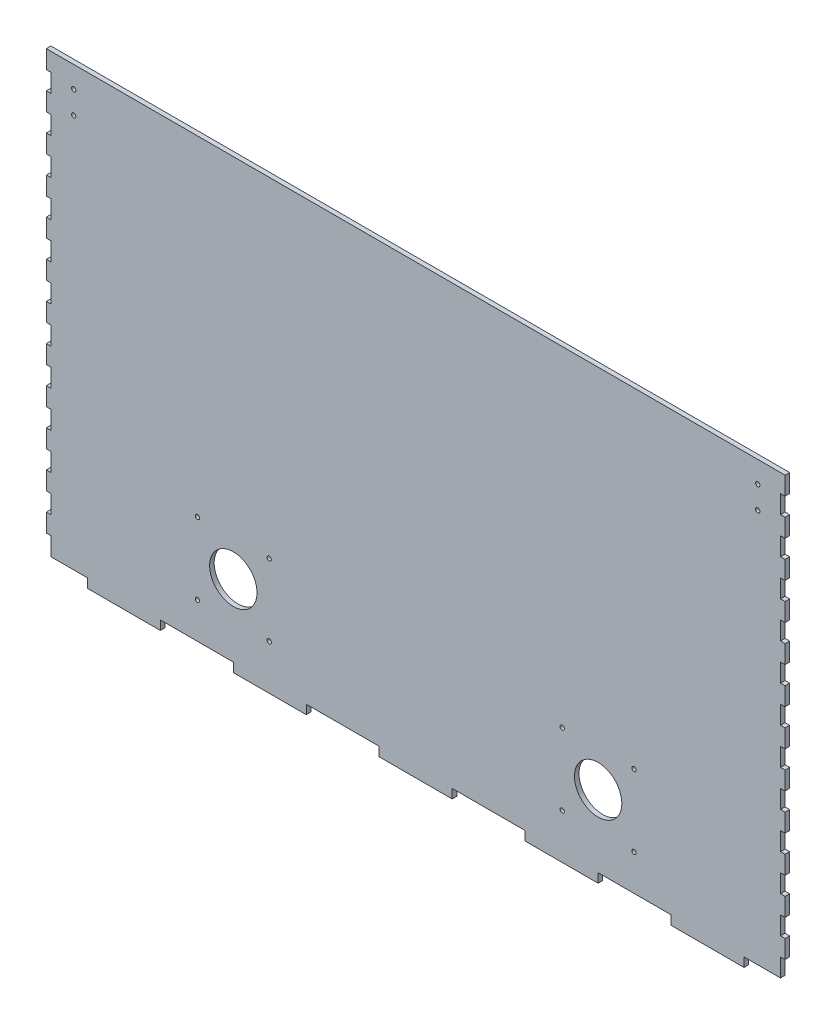
SolidWorks part; units mm, degrees
ref_plane "Front Plane" through (0, 0, 0) normal (0, 0, 1) x (1, 0, 0)
ref_plane "Top Plane" through (0, 0, 0) normal (0, 1, 0) x (1, 0, 0)
ref_plane "Right Plane" through (0, 0, 0) normal (1, 0, 0) x (0, 0, -1)
sketch "Sketch1" plane through (0, 0, 0) normal (0, 0, 1) x (1, 0, 0)
  line L0 (0, 0) -> (508, 0)
  line L1 (508, 0) -> (508, 304.8)
  line L2 (508, 304.8) -> (0, 304.8)
  line L3 (0, 304.8) -> (0, 0)
  line L4 (254, 304.8) -> (254, 0) construction
  line L5 (0, 304.8) -> (-3.175, 304.8)
  line L6 (-3.175, 304.8) -> (-3.175, 292.1)
  line L7 (-3.175, 292.1) -> (0, 292.1)
  line L8 (25.4, 0) -> (25.4, -6.35)
  line L9 (25.4, -6.35) -> (76.2, -6.35)
  line L10 (76.2, -6.35) -> (76.2, 0)
  line L13 (0, 279.4) -> (-3.175, 279.4)
  line L14 (-3.175, 279.4) -> (-3.175, 266.7)
  line L15 (-3.175, 266.7) -> (0, 266.7)
  line L17 (0, 254) -> (-3.175, 254)
  line L18 (-3.175, 254) -> (-3.175, 241.3)
  line L19 (-3.175, 241.3) -> (0, 241.3)
  line L21 (0, 228.6) -> (-3.175, 228.6)
  line L22 (-3.175, 228.6) -> (-3.175, 215.9)
  line L23 (-3.175, 215.9) -> (0, 215.9)
  line L25 (0, 203.2) -> (-3.175, 203.2)
  line L26 (-3.175, 203.2) -> (-3.175, 190.5)
  line L27 (-3.175, 190.5) -> (0, 190.5)
  line L29 (0, 177.8) -> (-3.175, 177.8)
  line L30 (-3.175, 177.8) -> (-3.175, 165.1)
  line L31 (-3.175, 165.1) -> (0, 165.1)
  line L33 (0, 152.4) -> (-3.175, 152.4)
  line L34 (-3.175, 152.4) -> (-3.175, 139.7)
  line L35 (-3.175, 139.7) -> (0, 139.7)
  line L37 (0, 127) -> (-3.175, 127)
  line L38 (-3.175, 127) -> (-3.175, 114.3)
  line L39 (-3.175, 114.3) -> (0, 114.3)
  line L41 (0, 101.6) -> (-3.175, 101.6)
  line L42 (-3.175, 101.6) -> (-3.175, 88.9)
  line L43 (-3.175, 88.9) -> (0, 88.9)
  line L45 (0, 76.2) -> (-3.175, 76.2)
  line L46 (-3.175, 76.2) -> (-3.175, 63.5)
  line L47 (-3.175, 63.5) -> (0, 63.5)
  line L49 (0, 50.8) -> (-3.175, 50.8)
  line L50 (-3.175, 50.8) -> (-3.175, 38.1)
  line L51 (-3.175, 38.1) -> (0, 38.1)
  line L53 (0, 25.4) -> (-3.175, 25.4)
  line L54 (-3.175, 25.4) -> (-3.175, 12.7)
  line L55 (-3.175, 12.7) -> (0, 12.7)
  line L57 (0, 304.8) -> (0, 279.4) construction
  line L59 (127, 0) -> (127, -6.35)
  line L60 (127, -6.35) -> (177.8, -6.35)
  line L61 (177.8, -6.35) -> (177.8, 0)
  line L63 (228.6, 0) -> (228.6, -6.35)
  line L64 (228.6, -6.35) -> (279.4, -6.35)
  line L65 (279.4, -6.35) -> (279.4, 0)
  line L67 (330.2, 0) -> (330.2, -6.35)
  line L68 (330.2, -6.35) -> (381, -6.35)
  line L69 (381, -6.35) -> (381, 0)
  line L70 (76.2, 0) -> (177.8, 0) construction
  line L72 (431.8, 0) -> (431.8, -6.35)
  line L73 (431.8, -6.35) -> (482.6, -6.35)
  line L74 (482.6, -6.35) -> (482.6, 0)
  line L76 (511.175, 12.7) -> (508, 12.7)
  line L77 (511.175, 25.4) -> (511.175, 12.7)
  line L78 (508, 25.4) -> (511.175, 25.4)
  line L80 (511.175, 38.1) -> (508, 38.1)
  line L81 (511.175, 50.8) -> (511.175, 38.1)
  line L82 (508, 50.8) -> (511.175, 50.8)
  line L84 (511.175, 63.5) -> (508, 63.5)
  line L85 (511.175, 76.2) -> (511.175, 63.5)
  line L86 (508, 76.2) -> (511.175, 76.2)
  line L88 (511.175, 88.9) -> (508, 88.9)
  line L89 (511.175, 101.6) -> (511.175, 88.9)
  line L90 (508, 101.6) -> (511.175, 101.6)
  line L92 (511.175, 114.3) -> (508, 114.3)
  line L93 (511.175, 127) -> (511.175, 114.3)
  line L94 (508, 127) -> (511.175, 127)
  line L96 (511.175, 139.7) -> (508, 139.7)
  line L97 (511.175, 152.4) -> (511.175, 139.7)
  line L98 (508, 152.4) -> (511.175, 152.4)
  line L100 (511.175, 165.1) -> (508, 165.1)
  line L101 (511.175, 177.8) -> (511.175, 165.1)
  line L102 (508, 177.8) -> (511.175, 177.8)
  line L104 (511.175, 190.5) -> (508, 190.5)
  line L105 (511.175, 203.2) -> (511.175, 190.5)
  line L106 (508, 203.2) -> (511.175, 203.2)
  line L108 (511.175, 215.9) -> (508, 215.9)
  line L109 (511.175, 228.6) -> (511.175, 215.9)
  line L110 (508, 228.6) -> (511.175, 228.6)
  line L112 (511.175, 241.3) -> (508, 241.3)
  line L113 (511.175, 254) -> (511.175, 241.3)
  line L114 (508, 254) -> (511.175, 254)
  line L116 (511.175, 266.7) -> (508, 266.7)
  line L117 (511.175, 279.4) -> (511.175, 266.7)
  line L118 (508, 279.4) -> (511.175, 279.4)
  line L120 (511.175, 292.1) -> (508, 292.1)
  line L121 (511.175, 304.8) -> (511.175, 292.1)
  line L122 (508, 304.8) -> (511.175, 304.8)
  dimension "D1" = 508
  dimension "D2" = 304.8
  dimension "D3" = 3.175
  dimension "D4" = 12.7
  dimension "D5" = 6.35
  dimension "D6" = 50.8
  dimension "D7" = 25.4
  dimension "D9" = 25.4
  dimension "D11" = 101.6
  dimension "D8" = 12
  dimension "D10" = 5
extrude "Boss-Extrude1" add sketch "Sketch1" along normal blind 3.175 contours L2 L3 L0 L1 | L9 L10 L0 L8 | L60 L61 L0 L59 | L64 L65 L0 L63 | L68 L69 L0 L67 | L73 L74 L0 L72 | L54 L55 L3 L53 | L50 L51 L3 L49 | L46 L47 L3 L45 | L42 L43 L3 L41 | L38 L39 L3 L37 | L34 L35 L3 L33 | L30 L31 L3 L29 | L26 L27 L3 L25 | L22 L23 L3 L21 | L18 L19 L3 L17 | L14 L15 L3 L13 | L6 L7 L3 L5 | L78 L1 L76 L77 | L82 L1 L80 L81 | L86 L1 L84 L85 | L90 L1 L88 L89 | L98 L1 L96 L97 | L94 L1 L92 L93 | L102 L1 L100 L101 | L106 L1 L104 L105 | L110 L1 L108 L109 | L114 L1 L112 L113 | L118 L1 L116 L117 | L122 L1 L120 L121
sketch "Sketch2" plane through (0, 0, 3.175) normal (0, 0, 1) x (1, 0, 0)
  line L0 (254, 304.8) -> (254, -6.35) construction
  line L1 (511.175, 304.8) -> (-3.175, 304.8) construction
  line L2 (228.6, -6.35) -> (279.4, -6.35) construction
  line L3 (0, 6.35) -> (254, 6.35) construction
  line L5 (0, 12.7) -> (0, 0) construction
  line L6 (127, 6.35) -> (127, 304.8) construction
  line L7 (110.5, 50) -> (143.5, 50) construction
  line L8 (76.2, 0) -> (127, 0) construction
  circle A0 centre (127, 50) radius 16.5
  circle A1 centre (102, 75) radius 1.5
  circle A2 centre (152, 75) radius 1.5
  circle A3 centre (152, 25) radius 1.5
  circle A4 centre (102, 25) radius 1.5
  circle A5 centre (381, 50) radius 16.5
  circle A6 centre (356, 75) radius 1.5
  circle A7 centre (356, 25) radius 1.5
  circle A8 centre (406, 25) radius 1.5
  circle A9 centre (406, 75) radius 1.5
  dimension "D1" = 33
  dimension "D2" = 3
  dimension "D3" = 25
  dimension "D4" = 25
  dimension "D5" = 50
extrude "Cut-Extrude1" cut sketch "Sketch2" against normal up to surface (3.175 mm away) up to face at (254, 125.5767, 0)
sketch "Sketch3" plane through (0, 0, 3.175) normal (0, 0, 1) x (1, 0, 0)
  line L1 (511.175, 304.8) -> (-3.175, 304.8) construction
  line L2 (254, 304.8) -> (254, -6.35) construction
  line L3 (228.6, -6.35) -> (279.4, -6.35) construction
  line L4 (-3.175, 304.8) -> (-3.175, 292.1) construction
  circle A0 centre (15.875, 289.8) radius 1.5
  circle A1 centre (15.875, 274.05) radius 1.5
  circle A2 centre (492.125, 289.8) radius 1.5
  circle A3 centre (492.125, 274.05) radius 1.5
  dimension "D1" = 3
  dimension "D2" = 3
  dimension "D3" = 19.05
  dimension "D4" = 15.75
  dimension "D5" = 15
extrude "Cut-Extrude2" cut sketch "Sketch3" against normal up to surface (3.175 mm away) up to face at (103.5, 75, 0)
equation "\"wall_thickness\"= 0.125in"
equation "\"base_thickness\"= 0.25in"
equation "\"D3@Sketch1\"=\"wall_thickness\""
equation "\"D5@Sketch1\"=\"base_thickness\""
equation "\"D1@Boss-Extrude1\"=\"wall_thickness\""
